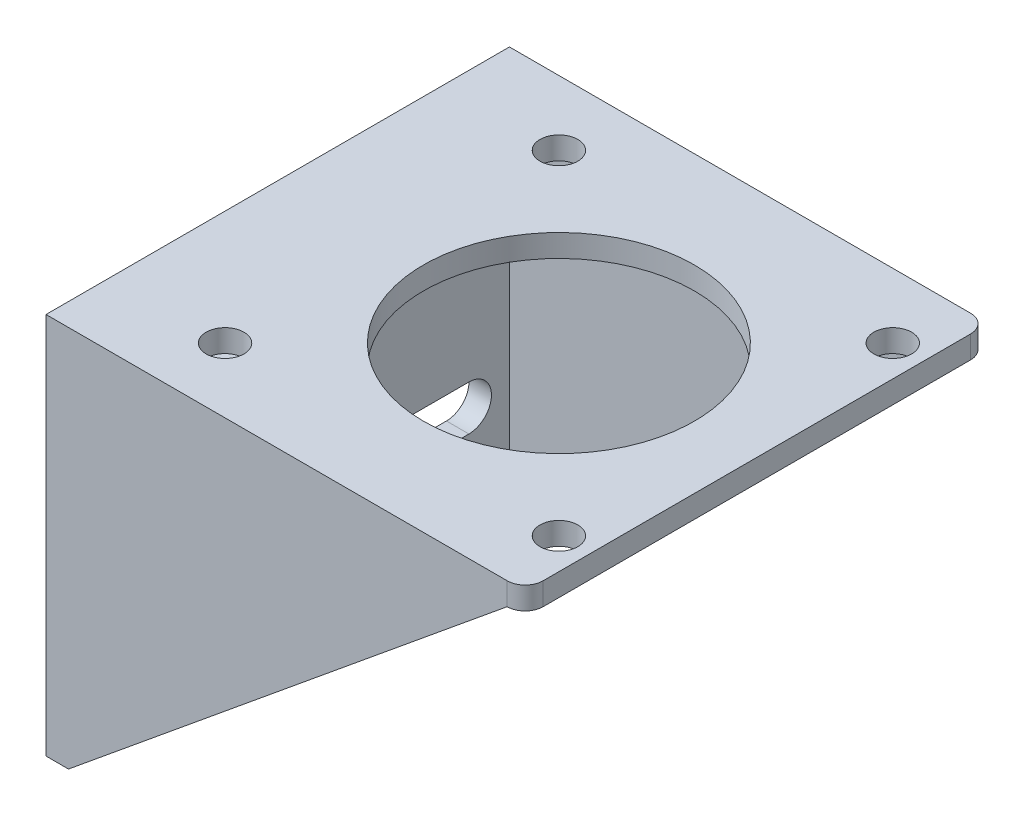
SolidWorks part; units mm, degrees
ref_plane "Front Plane" through (0, 0, 0) normal (0, 0, 1) x (1, 0, 0)
ref_plane "Top Plane" through (0, 0, 0) normal (0, 1, 0) x (1, 0, 0)
ref_plane "Right Plane" through (0, 0, 0) normal (1, 0, 0) x (0, 0, -1)
sketch "Sketch1" plane through (0, 0, 0) normal (0, 1, 0) x (1, 0, 0)
  line L0 (-26.2255, 26.2255) -> (-26.2255, -26.2255) construction
  line L1 (-26.2255, -26.2255) -> (26.2255, -26.2255) construction
  line L2 (26.2255, -26.2255) -> (26.2255, 26.2255) construction
  line L3 (26.2255, 26.2255) -> (-26.2255, 26.2255) construction
  line L4 (-26.2255, 26.2255) -> (26.2255, -26.2255) construction
  line L5 (-39.6875, 32.7025) -> (27.94, 32.7025)
  line L6 (27.94, 32.7025) -> (27.94, -32.7025)
  line L7 (27.94, -32.7025) -> (-39.6875, -32.7025)
  line L8 (-39.6875, -32.7025) -> (-39.6875, 32.7025)
  circle A0 centre (0, 0) radius 19.1135
  circle A1 centre (-23.5585, 23.5585) radius 2.667
  circle A2 centre (23.5585, 23.5585) radius 2.667
  circle A3 centre (-23.5585, -23.5585) radius 2.667
  circle A4 centre (23.5585, -23.5585) radius 2.667
  point P13 (0, 0)
  dimension "D1" = 38.227
  dimension "D2" = 5.334
  dimension "D3" = 52.451
  dimension "D4" = 27.94
  dimension "D5" = 32.7025
  dimension "D6" = 32.7025
  dimension "D7" = 39.6875
extrude "Boss-Extrude1" add sketch "Sketch1" along normal blind 3.175
fillet "Fillet1" radius 2.54 2 edges at (27.94, 1.5875, 32.7025) (27.94, 1.5875, -32.7025)
sketch "Sketch2" plane through (-39.6875, 0, 0) normal (-1, 0, 0) x (0, 0, 1)
  line L0 (-32.7025, 0) -> (-32.7025, -50.8)
  line L2 (32.7025, -50.8) -> (32.7025, 0)
  line L3 (-32.7025, 0) -> (32.7025, 0)
  line L4 (32.7025, -50.8) -> (-32.7025, -50.8)
  line L5 (0, 0) -> (0, -50.8) construction
  point P6 (0, -50.8)
  dimension "D1" = 50.8
extrude "Boss-Extrude2" add sketch "Sketch2" against normal blind 3.175
ref_plane "Plane1" through (-36.5125, 0, -32.7025) normal (0, -1, 0) x (-1, 0, 0)
sketch "Sketch7" plane through (0, 0, 32.7025) normal (0, 0, 1) x (1, 0, 0)
  line L0 (-36.5125, -50.8) -> (25.4, 0)
  line L1 (25.4, 0) -> (-36.5125, 0)
  line L2 (-91.5125, 0) -> (18.4875, 0) construction
  line L3 (-36.5125, 0) -> (-36.5125, -50.8)
extrude "Boss-Extrude5" add sketch "Sketch7" against normal blind 3.175
sketch "Sketch8" plane through (0, 0, -32.7025) normal (0, 0, -1) x (-1, 0, 0)
  line L0 (-25.4, 0) -> (36.5125, 0)
  line L1 (36.5125, 0) -> (36.5125, -50.8)
  line L2 (36.5125, -50.8) -> (-25.4, 0)
extrude "Boss-Extrude6" add sketch "Sketch8" against normal blind 3.175
sketch "Sketch9" plane through (-36.5125, 0, 0) normal (1, 0, 0) x (0, 0, -1)
  line L0 (-12.3825, -9.525) -> (23.8125, -9.525) construction
  line L1 (23.8125, -9.525) -> (23.8125, -34.925) construction
  line L2 (23.8125, -34.925) -> (-12.3825, -34.925) construction
  line L3 (-12.3825, -34.925) -> (-12.3825, -9.525) construction
  line L4 (29.5275, 0) -> (29.5275, -50.8) construction
  line L5 (32.7025, 0) -> (32.7025, -50.8) construction
  line L6 (-2.2225, -6.35) -> (-12.3825, -6.35)
  line L7 (-2.2225, -12.7) -> (-12.3825, -12.7)
  line L8 (-2.2225, -31.75) -> (-12.3825, -31.75)
  line L9 (-2.2225, -38.1) -> (-12.3825, -38.1)
  line L10 (23.8125, -38.1) -> (13.6525, -38.1)
  line L11 (23.8125, -31.75) -> (13.6525, -31.75)
  line L12 (23.8125, -6.35) -> (13.6525, -6.35)
  line L13 (23.8125, -12.7) -> (13.6525, -12.7)
  line L14 (-30.1625, 3.175) -> (30.1625, 3.175) construction
  circle A0 centre (23.8125, -9.525) radius 3.175
  circle A1 centre (-12.3825, -9.525) radius 3.175
  circle A2 centre (23.8125, -34.925) radius 3.175
  circle A3 centre (-12.3825, -34.925) radius 3.175
  circle A4 centre (-2.2225, -9.525) radius 3.175
  circle A5 centre (13.6525, -9.525) radius 3.175
  circle A6 centre (13.6525, -34.925) radius 3.175
  circle A7 centre (-2.2225, -34.925) radius 3.175
  point P36 (22.225, -13.8262)
  dimension "D1" = 6.35
  dimension "0.225" = 5.715
  dimension "D2" = 45.085
  dimension "D3" = 25.4
  dimension "D4" = 10.16
  dimension "D5" = 10.16
  dimension "D6" = 12.7
extrude "Cut-Extrude1" cut sketch "Sketch9" against normal blind 3.175 contours A4 L6 A1 L7 | A4 | A1 | A5 L13 A0 L12 | A5 | A0 | A2 | A6 L10 A2 L11 | A6 | A7 | A7 L8 A3 L9 | A3
equation "\"D5@Sketch1\"=1.1+1/8+1/16"
equation "\"D6@Sketch1\"=1.1+1/8+1/16"
equation "\"D2@Sketch9\"=2-0.125-0.1"
